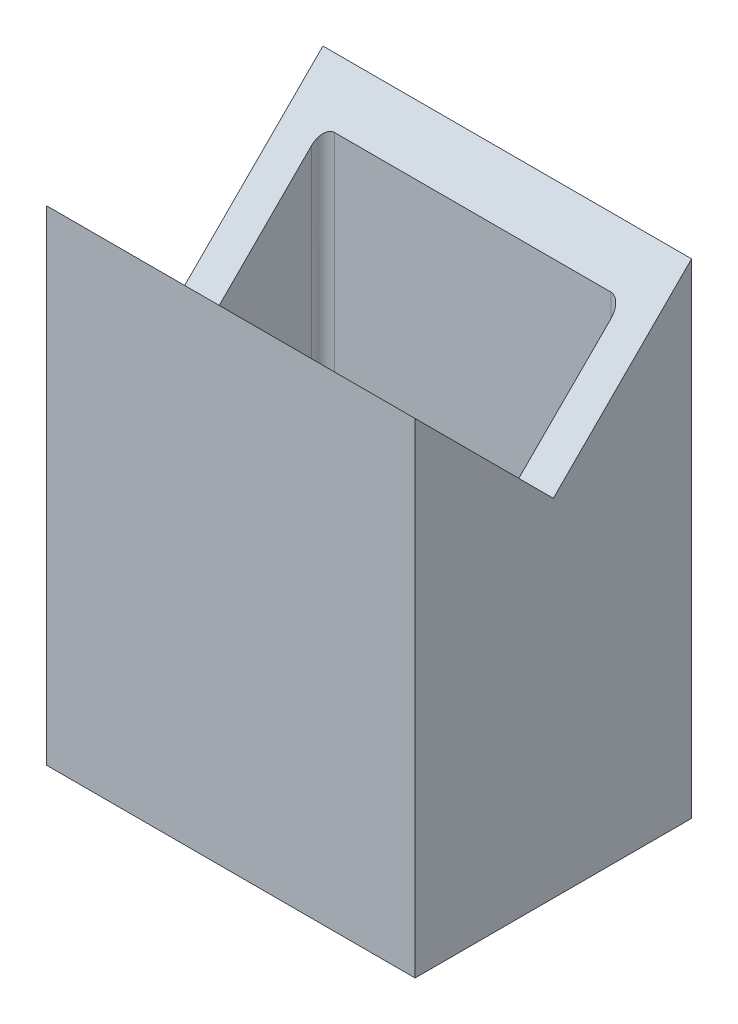
SolidWorks part; units mm, degrees
material "AISI 1015 Steel, Cold Drawn (SS)"
ref_plane "Front Plane" through (0, 0, 0) normal (0, 0, 1) x (1, 0, 0)
ref_plane "Top Plane" through (0, 0, 0) normal (0, 1, 0) x (1, 0, 0)
ref_plane "Right Plane" through (0, 0, 0) normal (1, 0, 0) x (0, 0, -1)
other "24x0.12x2x3"
sketch "Sketch1" plane through (0, 0, 0) normal (0, 1, 0) x (1, 0, 0)
  line L0 (0, 28.575) -> (0, 38.1) construction
  line L1 (-52.6132, -38.1) -> (52.6132, -38.1)
  line L2 (-50.8, 24.4227) -> (-50.8, -24.4227)
  line L3 (-39.9132, 38.1) -> (39.9132, 38.1)
  line L4 (50.8, -0.9773) -> (50.8, 0.9773)
  line L5 (-50.8, -38.1) -> (50.8, 38.1) construction
  line L6 (-50.8, 38.1) -> (50.8, -38.1) construction
  line L7 (-38.1, -28.575) -> (38.1, -28.575)
  line L8 (-41.275, -25.4) -> (-41.275, 25.4)
  line L9 (-38.1, 28.575) -> (38.1, 28.575)
  line L10 (41.275, -25.4) -> (41.275, 25.4)
  line L13 (41.275, 0) -> (50.8, 0) construction
  line L14 (0, -28.575) -> (0, -38.1) construction
  line L15 (-41.275, 0) -> (-50.8, 0) construction
  line L16 (-52.6132, -38.1) -> (-50.8, -38.1)
  line L17 (-50.8, -38.1) -> (-50.8, 24.4227)
  line L18 (-50.8, -24.4227) -> (-50.8, 38.1)
  line L19 (-50.8, 38.1) -> (-39.9132, 38.1)
  line L20 (39.9132, 38.1) -> (50.8, 38.1)
  line L21 (50.8, 38.1) -> (50.8, 0.9773)
  line L22 (50.8, -0.9773) -> (50.8, -38.1)
  line L23 (50.8, -38.1) -> (52.6132, -38.1)
  arc A7 (-38.1, -28.575) -> (-41.275, -25.4) centre (-38.1, -25.4) cw
  arc A8 (-41.275, 25.4) -> (-38.1, 28.575) centre (-38.1, 25.4) cw
  arc A9 (38.1, 28.575) -> (41.275, 25.4) centre (38.1, 25.4) cw
  arc A10 (41.275, -25.4) -> (38.1, -28.575) centre (38.1, -25.4) cw
  point P0 (0, 0)
  point P6 (0, 0)
  dimension "D4" = 3.175
  dimension "D1" = 9.525
  dimension "D2" = 76.2
  dimension "D3" = 101.6
extrude "Boss-Extrude1" add sketch "Sketch1" along normal blind 508 contours L22 L4 L21 L3 L18 L2 L17 L1 L10 A10 L7 A7 L8 A8 L9 A9
sketch "Sketch2" plane through (0, 0, -38.1) normal (0, 0, -1) x (-1, 0, 0)
  line L0 (38.1, 508) -> (-50.8, 419.1)
  line L1 (-50.8, 508) -> (-50.8, 0) construction
  line L2 (-50.8, 419.1) -> (-50.8, 508)
  line L3 (-50.8, 508) -> (38.1, 508)
  line L4 (50.8, 508) -> (-50.8, 508) construction
  dimension "D1" = 88.9
extrude "Cut-Extrude1" [suppressed] cut sketch "Sketch2" against normal through all
sketch "Sketch3" [suppressed] plane through (0, 0, -25.4) normal (0, 0, -1) x (-1, 0, 0)
  line L0 (38.1, 1738.9974) -> (38.1, 1828.8) construction
  line L1 (38.1, 1828.8) -> (38.1, 0) construction
  line L2 (-38.1, 1752.6) -> (-38.1, 0) construction
  line L4 (38.1, 1738.9974) -> (-38.1, 1662.7974) construction
  line L5 (38.1, 1828.8) -> (-38.1, 1752.6) construction
  line L6 (-38.1, 1752.6) -> (-38.1, 1662.7974) construction
  line L7 (-38.1, 1689.7382) -> (38.1, 1765.9382) construction
  line L8 (-20.2717, 1743.4876) -> (6.6691, 1770.4283) construction
  line L9 (-6.8013, 1783.8987) -> (38.1, 1738.9974) construction
  line L10 (11.1592, 1712.0567) -> (-2.3112, 1725.5271) construction
  line L11 (-2.3112, 1725.5271) -> (-20.2717, 1743.4876) construction
  line L12 (-20.2717, 1743.4876) -> (-33.742, 1756.958) construction
  line L13 (6.6691, 1770.4283) -> (38.1, 1801.8592) construction
  line L14 (-20.2717, 1743.4876) -> (-38.1, 1725.6592) construction
  line L16 (38.1, 1738.9974) -> (38.1, 1828.8) construction
  circle A7 centre (-11.2914, 1734.5073) radius 12.7
  circle A8 centre (15.6494, 1761.4481) radius 12.7
  dimension "D1" = 63.5
  dimension "D2" = 38.1
  dimension "D3" = 89.8026
  dimension "D4" = 45
  dimension "D6" = 25.4
extrude "Cut-Extrude2" [suppressed] cut sketch "Sketch3" against normal through all
sketch "Sketch6" plane through (0, 0, 38.1) normal (0, 0, 1) x (1, 0, 0)
  line L0 (0, 0) -> (0, 44.45) construction
  line L1 (0, 44.45) -> (6.35, 44.45) construction
  line L2 (6.35, 44.45) -> (6.35, 222.25) construction
  line L3 (-31.75, 222.25) -> (6.35, 222.25) construction
  line L4 (-50.8, 508) -> (-50.8, 0) construction
  line L5 (-31.75, 222.25) -> (-31.75, 44.45) construction
  line L6 (-31.75, 44.45) -> (0, 44.45) construction
  line L7 (4.7319, 222.25) -> (4.7319, 133.35) construction
  line L8 (4.7319, 133.35) -> (4.7319, 44.45) construction
  line L9 (-31.75, 222.25) -> (-31.75, 266.7) construction
  line L10 (-31.75, 266.7) -> (-31.75, 311.15) construction
  line L11 (-31.75, 311.15) -> (19.05, 311.15) construction
  line L12 (19.05, 311.15) -> (19.05, 266.7) construction
  line L13 (19.05, 266.7) -> (6.35, 222.25) construction
  circle A0 centre (-31.75, 222.25) radius 6.985
  circle A1 centre (6.35, 222.25) radius 6.985
  circle A2 centre (6.35, 133.35) radius 6.985
  circle A3 centre (-31.75, 133.35) radius 6.985
  circle A4 centre (-31.75, 44.45) radius 6.985
  circle A5 centre (6.35, 44.45) radius 6.985
  circle A6 centre (6.35, 177.8) radius 6.985
  circle A7 centre (-31.75, 177.8) radius 6.985
  circle A8 centre (-31.75, 88.9) radius 6.985
  circle A9 centre (6.35, 88.9) radius 6.985
  circle A10 centre (-31.75, 266.7) radius 6.985
  circle A12 centre (-31.75, 311.15) radius 6.985
  circle A13 centre (19.05, 311.15) radius 6.985
  circle A14 centre (19.05, 266.7) radius 6.985
  circle A15 centre (19.05, 266.7) radius 6.985
  point P30 (4.7319, 177.8)
  dimension "D4" = 13.97
  dimension "D7" = 44.45
  dimension "D1" = 38.1
  dimension "D2" = 19.05
  dimension "D3" = 44.45
  dimension "D5" = 44.45
  dimension "D6" = 44.45
  dimension "D8" = 44.45
  dimension "D9" = 44.45
extrude "Cut-Extrude5" [suppressed] cut sketch "Sketch6" against normal through all contours A13 | A10 | A1 | A7 | A2 | A8 | A5
sketch "Sketch7" plane through (0, 0, 38.1) normal (0, 0, 1) x (1, 0, 0)
  line L0 (-25.4, 419.1) -> (25.4, 419.1) construction
  line L1 (-50.8, 508) -> (50.8, 508) construction
  line L2 (25.4, 419.1) -> (25.4, 438.15) construction
  line L3 (25.4, 438.15) -> (25.4, 488.95) construction
  line L4 (-25.4, 488.95) -> (25.4, 488.95) construction
  line L5 (-50.8, 508) -> (-50.8, 0) construction
  line L6 (-25.4, 419.1) -> (-25.4, 508) construction
  line L7 (-25.4, 419.1) -> (-50.8, 419.1) construction
  line L8 (25.4, 419.1) -> (50.8, 419.1) construction
  line L9 (50.8, 508) -> (50.8, 0) construction
  line L10 (-50.8, 508) -> (50.8, 508) construction
  line L11 (25.4, 508) -> (25.4, 488.95) construction
  line L12 (25.4, 488.95) -> (0, 438.15) construction
  line L13 (-25.4, 438.15) -> (-25.4, 387.35) construction
  circle A0 centre (25.4, 488.95) radius 6.985
  circle A1 centre (25.4, 438.15) radius 6.985
  circle A2 centre (-25.4, 438.15) radius 6.985
  circle A3 centre (-25.4, 488.95) radius 6.985
  circle A4 centre (0, 488.95) radius 6.985
  circle A5 centre (0, 438.15) radius 6.985
  circle A6 centre (-25.4, 387.35) radius 6.985
  circle A7 centre (25.4, 387.35) radius 6.985
  dimension "D3" = 13.97
  dimension "D1" = 50.8
  dimension "D2" = 50.8
  dimension "D4" = 25.4
  dimension "D5" = 19.05
extrude "Cut-Extrude6" [suppressed] cut sketch "Sketch7" against normal up to surface (76.2 mm away) contours A2 | A6 | A3 | A0 | A1 | A7
pattern_linear "LPattern1" [suppressed] count 2 spacing 368.3
sketch "Sketch8" plane through (50.8, 0, 0) normal (1, 0, 0) x (0, 0, -1)
  line L0 (0, 95.4369) -> (-38.1, 133.5369)
  line L1 (-38.1, 508) -> (-38.1, 0) construction
  line L2 (0, 95.4369) -> (0, 0) construction
  line L5 (38.1, 508) -> (38.1, 0) construction
  line L8 (38.1, 133.5369) -> (0, 95.4369)
  line L9 (-38.1, 133.5369) -> (-38.1, 584.1412)
  line L10 (-38.1, 584.1412) -> (38.1, 584.1412)
  line L11 (38.1, 584.1412) -> (38.1, 133.5369)
  line L12 (-38.1, 508) -> (-38.1, 0) construction
  line L13 (38.1, 508) -> (38.1, 0) construction
  line L14 (38.1, 0) -> (-38.1, 0) construction
  line M7 (38.1, 0) -> (38.1, 508)
  line M9 (-38.1, 508) -> (-38.1, 0)
  line M11 (38.1, 508) -> (-38.1, 508)
  dimension "D1" = 45
  dimension "D3" = 95.4369
extrude "Cut-Extrude7" cut sketch "Sketch8" against normal up to surface (101.6 mm away) contours L8 L0 M7 M11 M9 up to face at (-50.8, 254, 0)
sketch "Sketch12" [suppressed] plane through (0, 0, 50.8) normal (0, 0, 1) x (1, 0, 0)
  line L0 (-19.05, 488.95) -> (-19.05, 469.9) construction
  line L1 (-38.1, 508) -> (38.1, 508) construction
  line L2 (-19.05, 469.9) -> (-19.05, 431.8) construction
  line L3 (-19.05, 431.8) -> (-19.05, 412.75) construction
  line L4 (-19.05, 412.75) -> (19.05, 412.75) construction
  line L5 (19.05, 412.75) -> (19.05, 431.8) construction
  line L6 (19.05, 431.8) -> (19.05, 469.9) construction
  line L7 (19.05, 469.9) -> (38.1, 469.9) construction
  line L8 (38.1, 508) -> (38.1, 0) construction
  line L9 (-19.05, 469.9) -> (-38.1, 469.9) construction
  line L10 (-38.1, 508) -> (-38.1, 0) construction
  line L11 (-19.05, 488.95) -> (-19.05, 508) construction
  circle A0 centre (-19.05, 431.8) radius 6.985
  circle A1 centre (19.05, 431.8) radius 6.985
  circle A2 centre (19.05, 469.9) radius 6.985
  circle A3 centre (-19.05, 469.9) radius 6.985
  dimension "D4" = 13.97
  dimension "D1" = 95.25
  dimension "D2" = 19.05
  dimension "D3" = 38.1
  dimension "D5" = 19.05
sketch "Sketch14" [suppressed] plane through (0, 0, 25.4) normal (0, 0, 1) x (1, 0, 0)
  line L0 (-38.1, 1828.8) -> (824.0046, 966.6954) construction
  line L1 (824.0046, 966.6954) -> (38.1, 180.7908) construction
  line L3 (38.1, 1752.6) -> (38.1, 0) construction
  line L4 (38.1, 180.7908) -> (6.8013, 149.4921)
  line L5 (6.8013, 149.4921) -> (-38.1, 194.3934)
  line L6 (-38.1, 1828.8) -> (-38.1, 0) construction
  line L7 (-38.1, 194.3934) -> (-38.1, 0)
  line L8 (-38.1, 0) -> (38.1, 0)
  line L9 (38.1, 0) -> (38.1, 180.7908)
  dimension "D1" = 1219.2
  dimension "D2" = 45
  dimension "D3" = 63.5
extrude "Cut-Extrude12" [suppressed] cut sketch "Sketch14" against normal through all contours L8 L9 L4 L5 L7
extrude "Cut-Extrude10" [suppressed] cut sketch "Sketch12" against normal up to surface (101.6 mm away)
pattern_linear "LPattern2" [suppressed] count 2 spacing 393.7
sketch "Sketch15" [suppressed] plane through (0, 0, 25.4) normal (0, 0, 1) x (1, 0, 0)
  line L0 (-38.1, 889) -> (392.9523, 457.9477) construction
  line L1 (392.9523, 457.9477) -> (-38.1, 26.8954) construction
  line L2 (-38.1, 889) -> (-38.1, 0) construction
  line L3 (-38.1, 26.8954) -> (-38.1, 0)
  line L4 (-38.1, 0) -> (38.1, 0)
  line L5 (38.1, 0) -> (38.1, 103.0954)
  line L6 (38.1, 812.8) -> (38.1, 0) construction
  line L7 (38.1, 103.0954) -> (-38.1, 26.8954) construction
  line L8 (38.1, 103.0954) -> (-38.1, 26.8954)
  dimension "D1" = 609.6
extrude "Cut-Extrude13" [suppressed] cut sketch "Sketch15" against normal through all
pattern_linear "LPattern3" [suppressed] count 2 spacing 609.6
hole_wizard "1 (1.05) Diameter Hole1" [suppressed] positions "Sketch16" profile "Sketch17" hole size "1" standard "ANSI Inch"
sketch "Sketch16" plane through (886.8664, 921.7941, 34.925) normal (0, 0, 1) x (0.7071, 0.7071, 0)
  point P0 (-1111.7329, 120.65)
sketch "Sketch17" plane through (15.4401, 220.9927, 34.925) normal (1, 0, 0) x (0, -1, 0)
  line L0 (0, 0) -> (0, 68.3365)
  line L1 (0, 68.3365) -> (13.335, 60.324)
  line L2 (13.335, 60.324) -> (13.335, 0)
  line L3 (13.335, 0) -> (0, 0)
  line L4 (0, 68.3365) -> (-13.335, 60.324) construction
  line L5 (0, -6.35) -> (0, 107.95) construction
  dimension "Hole Dia." = 26.67
  dimension "Hole Depth" = 60.324
  dimension "Drill Angle" = 118
